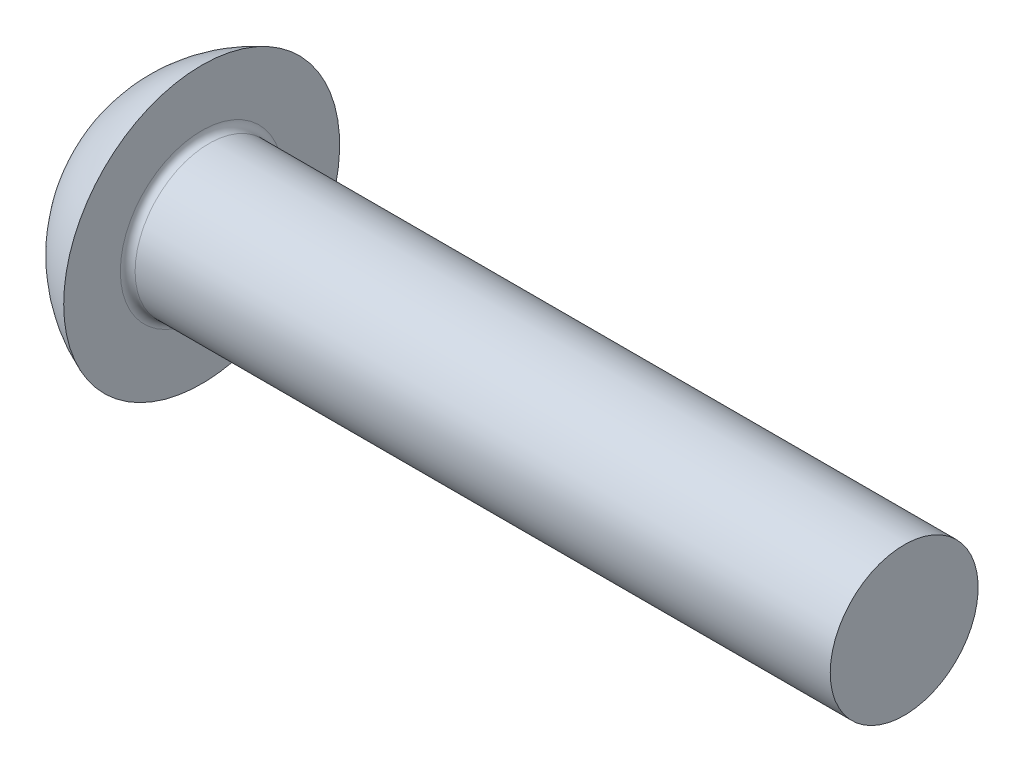
SolidWorks part; units mm, degrees
ref_plane "前视" through (0, 0, 0) normal (0, 0, 1) x (1, 0, 0)
ref_plane "上视" through (0, 0, 0) normal (0, 1, 0) x (1, 0, 0)
ref_plane "右视" through (0, 0, 0) normal (1, 0, 0) x (0, 0, -1)
sketch "尺寸草图" plane through (0, 0, 0) normal (0, 0, 1) x (1, 0, 0)
  line L0 (0, 0) -> (28.5, 0)
  point P3 (11.35, 0)
  point P4 (6, 0)
  point P5 (6, 0)
  point P6 (14.25, 0)
  point P7 (24.66, 0)
  point P8 (0.3, 0)
  point P9 (13.3856, 0)
  point P10 (42.419, 0)
  dimension "l" = 28.5
  dimension "dk" = 11.35
  dimension "d" = 6
  dimension "r" = 6
  dimension "k" = 3.84
  dimension "RR" = 0.3
sketch "草图1" plane through (0, 0, 0) normal (0, 0, 1) x (1, 0, 0)
  line L0 (-30.7302, 0) -> (31.1073, 0) construction
  line L1 (3.84, 5.5977) -> (3.84, 3.3)
  line L2 (4.14, 3) -> (32.34, 3)
  line L3 (32.34, 3) -> (32.34, 0)
  line L4 (32.34, 0) -> (0, 0)
  arc A0 (0, 0) -> (3.84, 5.5977) centre (6, 0) cw
  arc A1 (3.84, 3.3) -> (4.14, 3) centre (4.14, 3.3) ccw
  dimension "D1" = 0.3
  dimension "D3" = 6
  dimension "D2" = 28.5
  dimension "D4" = 3
  dimension "D5" = 3.84
revolve "基体-旋转" add sketch "草图1" angle 360 about L0
equation "\"D4@草图1\" = \"d@尺寸草图\" / 2"
equation "\"D2@草图1\" = \"l@尺寸草图\""
equation "\"D1@草图1\" = \"RR@尺寸草图\""
equation "\"D3@草图1\" = \"r@尺寸草图\""
equation "\"D5@草图1\" = \"k@尺寸草图\""
